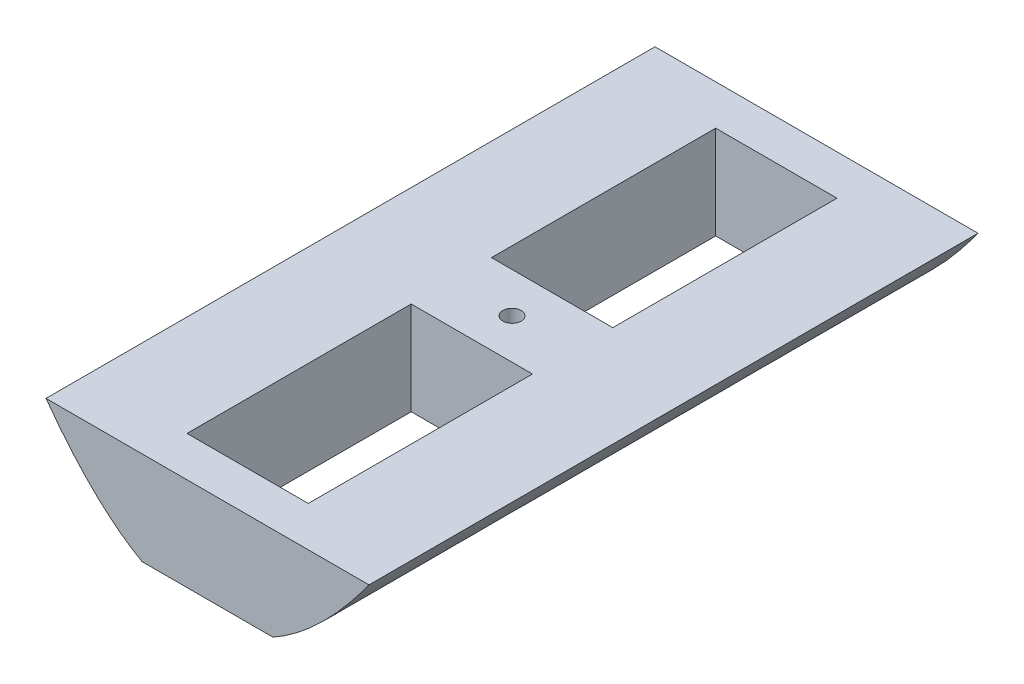
SolidWorks part; units mm, degrees
ref_plane "Front Plane" through (0, 0, 0) normal (0, 0, 1) x (1, 0, 0)
ref_plane "Top Plane" through (0, 0, 0) normal (0, 1, 0) x (1, 0, 0)
ref_plane "Right Plane" through (0, 0, 0) normal (1, 0, 0) x (0, 0, -1)
sketch "Sketch2" plane through (0, 0, 0) normal (0, 0, 1) x (1, 0, 0)
  line L0 (-127, 127) -> (127, 127)
  spline S0 degree 2 poles (-143.0272, 161.0769) (0, -161.0769) (143.0272, 161.0769) knots 0 0 0 1 1 1 construction
  spline S1 degree 2 poles (-127, 127) (0, -127) (127, 127) knots 0.056028 0.056028 0.056028 0.943972 0.943972 0.943972
extrude "Boss-Extrude2" add sketch "Sketch2" along normal blind 331.382
sketch "Sketch3" plane through (0, 127, 0) normal (0, 1, 0) x (1, 0, 0)
  line L0 (0, -309.5365) -> (0, 0) construction
  line L1 (-33, -21.8455) -> (33, -21.8455)
  line L2 (-33, -21.8455) -> (-33, -143.8455)
  line L3 (-33, -143.8455) -> (33, -143.8455)
  line L4 (33, -21.8455) -> (33, -143.8455)
  line L5 (-33, -187.5365) -> (33, -187.5365)
  line L6 (-33, -187.5365) -> (-33, -309.5365)
  line L7 (-33, -309.5365) -> (33, -309.5365)
  line L8 (33, -187.5365) -> (33, -309.5365)
  line L9 (-127, -165.691) -> (127, -165.691) construction
  line L10 (-127, -331.382) -> (-127, 0) construction
  line L11 (127, -331.382) -> (127, 0) construction
  line L12 (-33, -143.8455) -> (-33, -165.691) construction
  line L13 (33, -187.5365) -> (33, -165.691) construction
  line L14 (-33, -21.8455) -> (-33, 0) construction
  line L15 (127, 0) -> (-127, 0) construction
  circle A0 centre (0, -165.691) radius 5
  dimension "D3" = 10
  dimension "D1" = 122
  dimension "D2" = 66
extrude "Cut-Extrude2" cut sketch "Sketch3" against normal through all
sketch "Sketch4" plane through (0, 0, 0) normal (0, 0, -1) x (-1, 0, 0)
  line L1 (-40, 10) -> (40, 10)
  line L2 (-40, 10) -> (-40, 0)
  line L3 (-40, 0) -> (40, 0)
  line L4 (40, 10) -> (40, 0)
  dimension "D1" = 10
  dimension "D2" = 80
extrude "Cut-Extrude3" cut sketch "Sketch4" against normal through all
sketch "Sketch5" plane through (0, 0, 331.382) normal (0, 0, 1) x (1, 0, 0)
  line L0 (0, 0) -> (0, 60.8) construction
  line L1 (-130, 130.8) -> (130, 130.8)
  line L2 (-130, 130.8) -> (-130, 60.8)
  line L3 (-130, 60.8) -> (130, 60.8)
  line L4 (130, 130.8) -> (130, 60.8)
  dimension "D1" = 60.8
  dimension "D2" = 260
  dimension "D3" = 70
extrude "Cut-Extrude4" cut sketch "Sketch5" against normal through all
